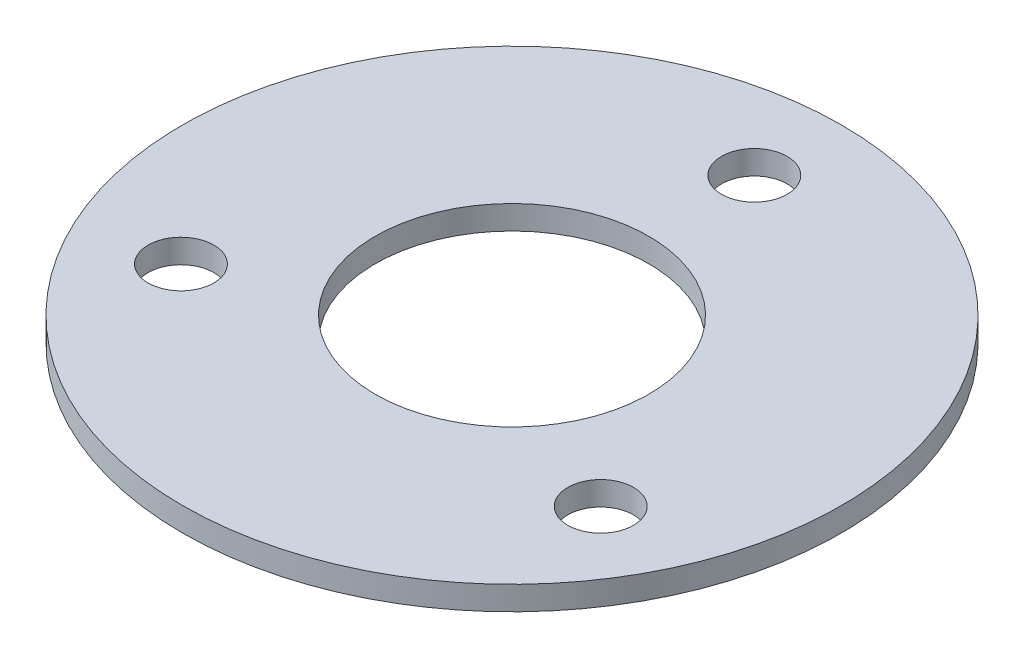
SolidWorks part; units mm, degrees
ref_plane "Front Plane" through (0, 0, 0) normal (0, 0, 1) x (1, 0, 0)
ref_plane "Top Plane" through (0, 0, 0) normal (0, 1, 0) x (1, 0, 0)
ref_plane "Right Plane" through (0, 0, 0) normal (1, 0, 0) x (0, 0, -1)
sketch "Sketch1" plane through (0, 0, 0) normal (0, 1, 0) x (1, 0, 0)
  circle A0 centre (0, 0) radius 21.59
  circle A1 centre (0, 0) radius 8.9662
  circle A2 centre (0, 15.875) radius 2.1526
  circle A3 centre (13.7482, -7.9375) radius 2.1527
  circle A4 centre (-13.7482, -7.9375) radius 2.1527
  point P12 (0, 0)
  dimension "D1" = 43.18
  dimension "D2" = 17.9324
  dimension "D3" = 4.3053
  dimension "D4" = 15.875
  dimension "D5" = 3
extrude "Boss-Extrude1" add sketch "Sketch1" along normal blind 1.5621
